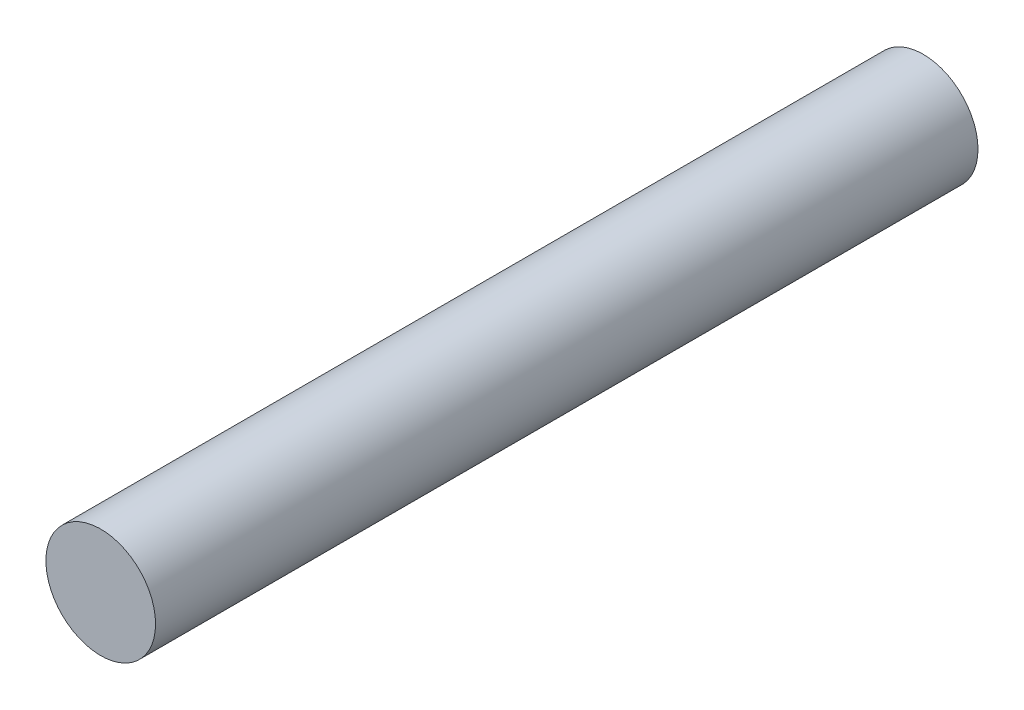
SolidWorks part; units mm, degrees
ref_plane "Ebene vorne" through (0, 0, 0) normal (0, 0, 1) x (1, 0, 0)
ref_plane "Ebene oben" through (0, 0, 0) normal (0, 1, 0) x (1, 0, 0)
ref_plane "Ebene rechts" through (0, 0, 0) normal (1, 0, 0) x (0, 0, -1)
sketch "Skizze1" plane through (0, 0, 0) normal (0, 0, 1) x (1, 0, 0)
  circle A0 centre (0, 0) radius 10
  dimension "D1" = 20
extrude "Aufsatz-Linear austragen1" add sketch "Skizze1" along normal blind 150
